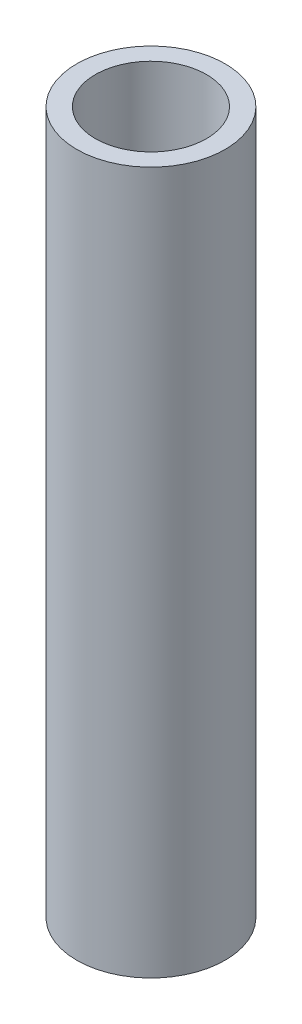
SolidWorks part; units mm, degrees
material "Tin Bearing Bronze"
ref_plane "Front" through (0, 0, 0) normal (0, 0, 1) x (1, 0, 0)
ref_plane "Top" through (0, 0, 0) normal (0, 1, 0) x (1, 0, 0)
ref_plane "Right" through (0, 0, 0) normal (1, 0, 0) x (0, 0, -1)
sketch "Sketch1" plane through (0, 0, 0) normal (0, 1, 0) x (1, 0, 0)
  circle A0 centre (0, 0) radius 4.7752
  circle A1 centre (0, 0) radius 6.3754
  circle A2 centre (0, 0) radius 8.7312
  dimension "ID" = 9.5504
  dimension "OD" = 12.7508
  dimension "FlangeOD" = 17.4625
sketch "Sketch2" plane through (0, 0, 0) normal (0, 1, 0) x (1, 0, 0)
  circle A0 centre (0, 0) radius 4.7752 construction
  circle A1 centre (0, 0) radius 6.3754 construction
  circle A2 centre (0, 0) radius 4.7752
  circle A3 centre (0, 0) radius 6.3754
extrude "Boss-Extrude1" add sketch "Sketch2" along normal blind 60.325
sketch "Sketch3" plane through (0, 0, 0) normal (0, 1, 0) x (1, 0, 0)
  circle A0 centre (0, 0) radius 8.7312 construction
  circle A1 centre (0, 0) radius 6.3754 construction
  circle A2 centre (0, 0) radius 8.7312
  circle A3 centre (0, 0) radius 6.3754
